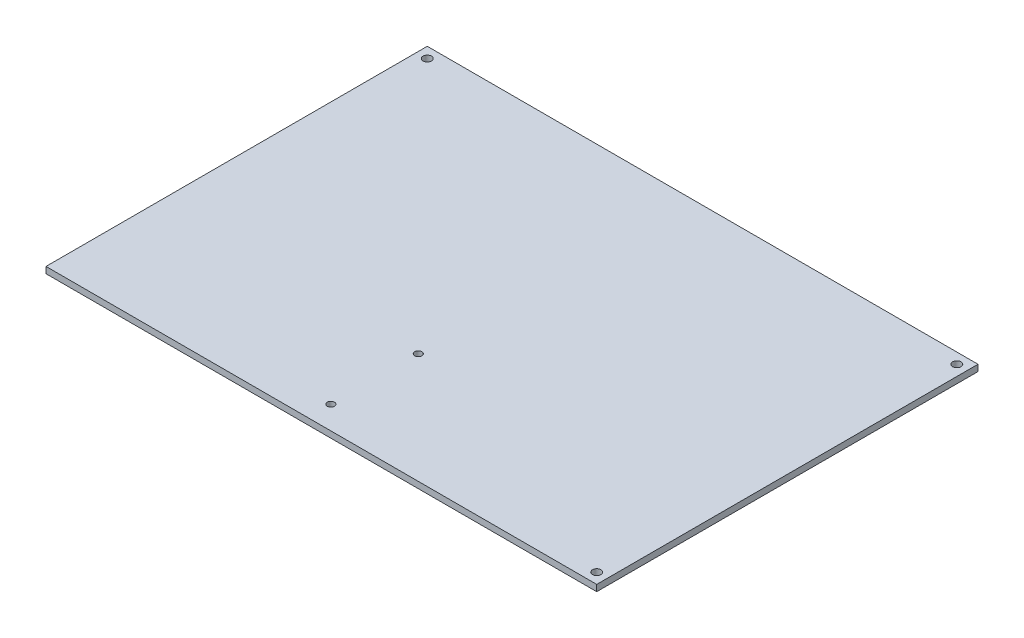
SolidWorks part; units mm, degrees
ref_plane "Front Plane" through (0, 0, 0) normal (0, 0, 1) x (1, 0, 0)
ref_plane "Top Plane" through (0, 0, 0) normal (0, 1, 0) x (1, 0, 0)
ref_plane "Right Plane" through (0, 0, 0) normal (1, 0, 0) x (0, 0, -1)
sketch "Sketch1" plane through (0, 0, 0) normal (0, 1, 0) x (1, 0, 0)
  line L1 (130, 90) -> (-130, 90)
  line L2 (130, 90) -> (130, -90)
  line L3 (130, -90) -> (-130, -90)
  line L4 (-130, 90) -> (-130, -90)
  line L5 (130, 90) -> (-130, -90) construction
  line L6 (130, -90) -> (-130, 90) construction
  point P0 (0, 0)
  dimension "D1" = 180
  dimension "D2" = 260
extrude "Boss-Extrude1" add sketch "Sketch1" along normal blind 3
sketch "Sketch2" plane through (0, 3, 0) normal (0, 1, 0) x (1, 0, 0)
  line L0 (-130, -90) -> (130, -90) construction
  line L1 (130, -90) -> (130, 90) construction
  line L2 (130, 90) -> (-130, -90) construction
  line L3 (0, 90) -> (0, -90) construction
  line L4 (130, 90) -> (-130, 90) construction
  line L5 (-130, 0) -> (130, 0) construction
  line L6 (-130, 90) -> (-130, -90) construction
  circle A0 centre (125, -85) radius 2
  circle A1 centre (125, 85) radius 2
  circle A2 centre (-125, 85) radius 2
  dimension "D1" = 4
  dimension "D2" = 5
  dimension "D3" = 5
extrude "Cut-Extrude1" cut sketch "Sketch2" against normal through all
sketch "Sketch3" plane through (0, 3, 0) normal (0, 1, 0) x (1, 0, 0)
  line L0 (-35, -90) -> (-35, 90) construction
  line L1 (-130, -90) -> (130, -90) construction
  line L2 (130, 90) -> (-130, 90) construction
  line L3 (-130, 90) -> (-130, -90) construction
  circle A0 centre (-6.425, -79.1006) radius 1.7
  circle A1 centre (-6.425, -37.8256) radius 1.7
  point P10 (0, 0)
  dimension "D2" = 41.275
  dimension "D1" = 95
  dimension "D3" = 28.575
extrude "Cut-Extrude2" cut sketch "Sketch3" against normal blind 10
